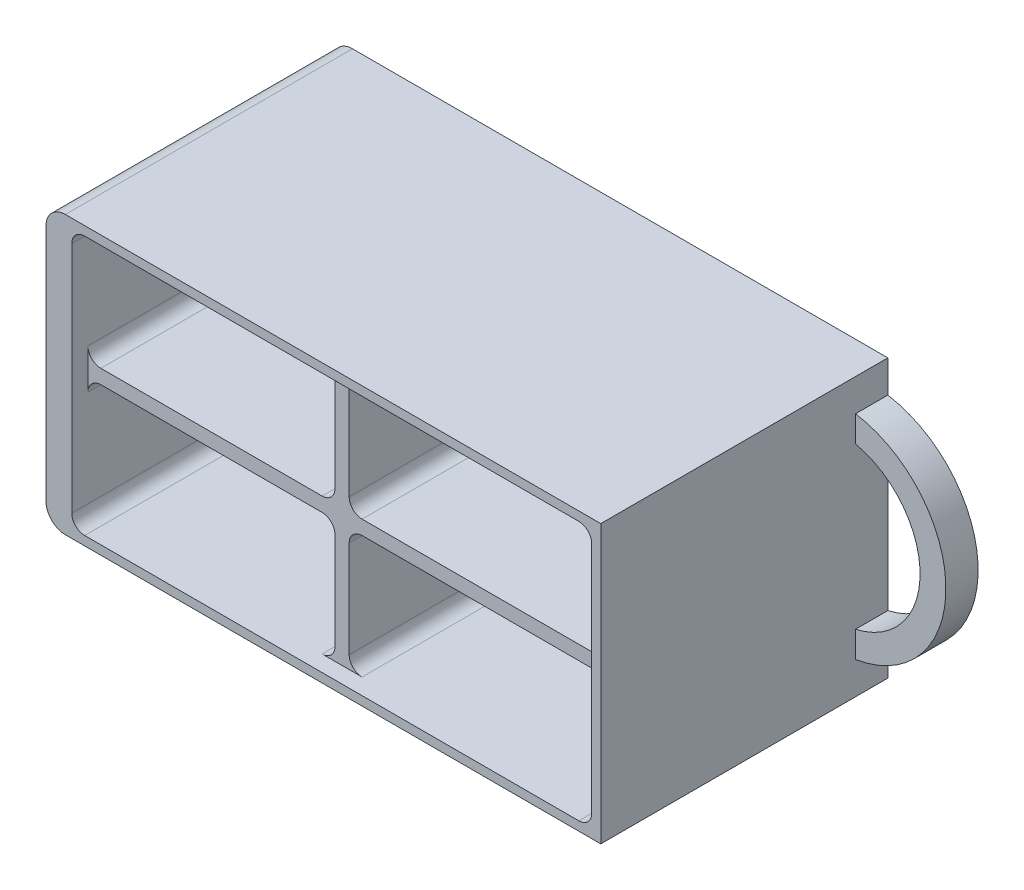
SolidWorks part; units mm, degrees
ref_plane "Спереди" through (0, 0, 0) normal (0, 0, 1) x (1, 0, 0)
ref_plane "Сверху" through (0, 0, 0) normal (0, 1, 0) x (1, 0, 0)
ref_plane "Справа" through (0, 0, 0) normal (1, 0, 0) x (0, 0, -1)
ref_plane "Плоскость4" through (0, 0, 22.25) normal (0, 0, 1) x (1, 0, 0)
sketch "Эскиз1" plane through (0, 0, 22.25) normal (0, 0, 1) x (1, 0, 0)
  line L0 (90, -21.5) -> (90, 21.5)
  line L1 (90, 21.5) -> (4, 21.5)
  line L2 (4, 21.5) -> (4, -21.5)
  line L3 (4, -21.5) -> (90, -21.5)
extrude "Бобышка-Вытянуть1" add sketch "Эскиз1" against normal blind 39.5
sketch "Эскиз2" plane through (0, 0, -17.25) normal (0, 0, -1) x (-1, 0, 0)
  line L0 (-90, -21.5) -> (-90, -16.5)
  line L1 (-90, 16.5) -> (-90, 21.5)
  line L2 (-90, 21.5) -> (-4, 21.5)
  line L3 (-4, 21.5) -> (-4, -21.5)
  line L4 (-4, -21.5) -> (-90, -21.5)
  line L5 (-90, -12.4284) -> (-90, 12.4284)
  arc A0 (-90, -16.5) -> (-90, 16.5) centre (-87.2768, 0) cw
  arc A1 (-90, 12.4284) -> (-90, -12.4284) centre (-87.2768, 0) ccw
extrude "Бобышка-Вытянуть2" add sketch "Эскиз2" along normal blind 5
sketch "Эскиз3" plane through (0, 0, 22.25) normal (0, 0, 1) x (1, 0, 0)
  line L0 (88.6, -20.1) -> (88.6, 20.1)
  line L1 (88.6, 20.1) -> (8, 20.1)
  line L2 (8, 20.1) -> (8, -20.1)
  line L3 (8, -20.1) -> (88.6, -20.1)
extrude "Вырез-Вытянуть1" cut sketch "Эскиз3" against normal blind 43.6
hole_wizard "Диаметр отверстия Ø8.3 (8.3)1" positions "Эскиз5" profile "Эскиз4" hole size "Ø8.3" standard "Ansi Metric"
sketch "Эскиз5" plane through (4, 0, 0) normal (-1, 0, 0) x (0, 0, 1)
  point P0 (0, 0)
sketch "Эскиз4" plane through (4, 0, 0) normal (0, 1, 0) x (0, 0, 1)
  line L0 (0, 0) -> (0, 3.2)
  line L1 (0, 3.2) -> (4.15, 3.2)
  line L2 (4.15, 3.2) -> (4.15, 0)
  line L5 (4.15, 0) -> (0, 0)
  line L10 (0, 3.2) -> (-4.15, 3.2) construction
  line L11 (0, -6.35) -> (0, 107.95) construction
  dimension "Диаметр отверстия" = 8.3
  dimension "Глубина отверстия" = 3.2
  dimension "Угол заточки сверла" = 180
fillet "Скругление1" radius 3 2 edges at (4, -21.5, 0) (4, 21.5, 0)
sketch "Эскиз6" plane through (4, 0, 0) normal (-1, 0, 0) x (0, 0, 1)
  circle A0 centre (0, 0) radius 4.15 construction
  circle A1 centre (0, 0) radius 4.15
extrude "Бобышка-Вытянуть3" add sketch "Эскиз6" against normal blind 4
sketch "Эскиз7" plane through (0, 0, -22.25) normal (0, 0, -1) x (-1, 0, 0)
  line L1 (-90, -12.4284) -> (-90, 12.4284) construction
  line L2 (-90, 0) -> (-4.8, 0) construction
  line L3 (-90, -1.1) -> (-90, 1.1)
  line L4 (-4, 0) -> (-4, 1.1)
  line L5 (-4, -18.5) -> (-4, 18.5) construction
  line L6 (-4, 0) -> (-4, -1.1)
  line L7 (-90, -1.1) -> (-4, -1.1)
  line L8 (-4, 1.1) -> (-90, 1.1)
  line L9 (-47.4, -27.2189) -> (-47.4, 27.2189) construction
  line L12 (-90, -21.5) -> (-7, -21.5) construction
  line L13 (-48.5, 21.5) -> (-46.3, 21.5)
  line L14 (-48.5, 21.5) -> (-48.5, -21.5)
  line L15 (-48.5, -21.5) -> (-46.3, -21.5)
  line L16 (-46.3, 21.5) -> (-46.3, -21.5)
  line L17 (-48.5, 21.5) -> (-46.3, -21.5) construction
  line L18 (-48.5, -21.5) -> (-46.3, 21.5) construction
  point P0 (-90, 0)
  point P7 (-90, 0)
  point P9 (-47.4, 0)
  point P17 (-47.4, 0)
  dimension "D1" = 1.1
  dimension "D2" = 1.1
  dimension "D3" = 42.6
  dimension "D4" = 2.2
extrude "Бобышка-Вытянуть4" add sketch "Эскиз7" against normal blind 42 contours L8 L3 L7 L6 L4
sketch "Эскиз10" plane through (0, 0, -22.25) normal (0, 0, -1) x (-1, 0, 0)
  line L0 (-47.4, 30.6908) -> (-47.4, -26.5541) construction
  line L2 (0, 0) -> (-118.0019, 0) construction
  line L3 (-90, -21.5) -> (-7, -21.5) construction
  line L4 (-48.5, 21.5) -> (-46.3, 21.5)
  line L5 (-48.5, 21.5) -> (-48.5, -21.5)
  line L6 (-48.5, -21.5) -> (-46.3, -21.5)
  line L7 (-46.3, 21.5) -> (-46.3, -21.5)
  line L8 (-48.5, 21.5) -> (-46.3, -21.5) construction
  line L9 (-48.5, -21.5) -> (-46.3, 21.5) construction
  point P4 (-47.4, 0)
  dimension "D1" = 42.6
  dimension "D2" = 18.5
  dimension "D3" = 2.2
extrude "Бобышка-Вытянуть5" add sketch "Эскиз10" against normal blind 42
fillet "Скругление2" radius 2 32 edges at (68.55, -1.1, -21.35) (88.6, -10.6, -21.35) (68.55, -20.1, -21.35) (48.5, -10.6, -21.35) (68.55, 20.1, -21.35) (88.6, 10.6, -21.35) (68.55, 1.1, -21.35) (48.5, 10.6, -21.35) (27.15, -20.1, -21.35) (8, -10.6, -21.35) (27.15, -1.1, -21.35) (46.3, -10.6, -21.35) (27.15, 1.1, -21.35) (8, 10.6, -21.35) (27.15, 20.1, -21.35) (46.3, 10.6, -21.35) (48.5, -20.1, -0.8) (88.6, -20.1, 0.45) (88.6, -1.1, -0.8) (48.5, -1.1, -0.8) (48.5, 1.1, -0.8) (88.6, 1.1, -0.8) (88.6, 20.1, 0.45) (48.5, 20.1, -0.8) (46.3, 1.1, -0.8) (46.3, 20.1, -0.8) (46.3, -20.1, -0.8) (46.3, -1.1, -0.8) (8, -20.1, 0.45) (8, -1.1, -0.8) (8, 1.1, -0.8) (8, 20.1, 0.45)
